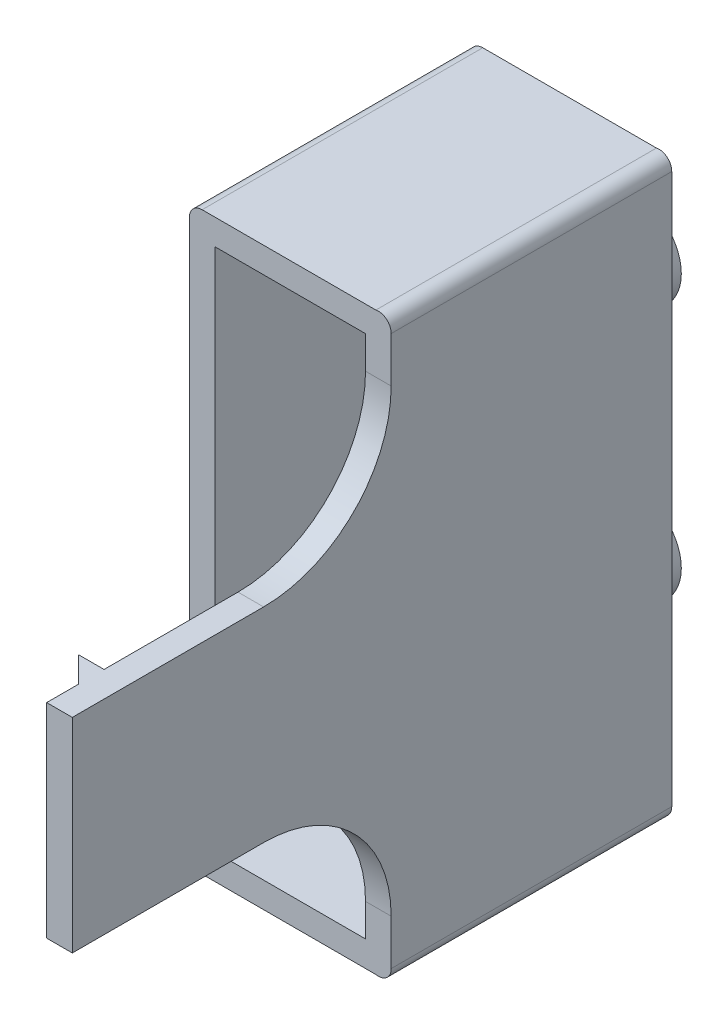
SolidWorks part; units mm, degrees
ref_plane "Front Plane" through (0, 0, 0) normal (0, 0, 1) x (1, 0, 0)
ref_plane "Top Plane" through (0, 0, 0) normal (0, 1, 0) x (1, 0, 0)
ref_plane "Right Plane" through (0, 0, 0) normal (1, 0, 0) x (0, 0, -1)
sketch "Sketch1" plane through (0, 0, 0) normal (0, 0, 1) x (1, 0, 0)
  circle A0 centre (0, -9.9992) radius 3.66
  circle A1 centre (0, 9.9992) radius 3.66
  circle A2 centre (0, -9.9992) radius 1.65
  circle A3 centre (0, 9.9992) radius 1.65
extrude "Boss-Extrude1" add sketch "Sketch1" along normal blind 5
sketch "Sketch2" plane through (0, 0, 5) normal (0, 0, 1) x (1, 0, 0)
  line L1 (-6.91, 22.56) -> (6.71, 22.56)
  line L2 (-7.91, 21.56) -> (-7.91, -21.56)
  line L3 (-6.91, -22.56) -> (6.71, -22.56)
  line L4 (7.91, 21.56) -> (7.91, -21.56)
  arc A0 (6.71, -22.56) -> (7.91, -21.56) centre (6.9102, -21.5802) ccw
  arc A1 (-7.91, -21.56) -> (-6.91, -22.56) centre (-6.91, -21.56) ccw
  arc A2 (6.71, 22.56) -> (7.91, 21.56) centre (6.9102, 21.5802) cw
  arc A3 (-6.91, 22.56) -> (-7.91, 21.56) centre (-6.91, 21.56) ccw
  circle A4 centre (0, 9.9992) radius 1.65
  circle A5 centre (0, -9.9992) radius 1.65
extrude "Boss-Extrude2" add sketch "Sketch2" along normal blind 22
sketch "Sketch3" plane through (0, 0, 27) normal (0, 0, 1) x (1, 0, 0)
  line L1 (-5.9, 20.55) -> (5.9, 20.55)
  line L2 (-5.9, 20.55) -> (-5.9, -20.55)
  line L3 (-5.9, -20.55) -> (5.9, -20.55)
  line L4 (5.9, 20.55) -> (5.9, -20.55)
extrude "Cut-Extrude1" cut sketch "Sketch3" against normal offset from surface (20 mm away) 2 up to face at (-0.0417, 0, 5)
sketch "Sketch4" plane through (0, 0, 27) normal (0, 0, 1) x (1, 0, 0)
  line L1 (5.9, 8) -> (7.91, 8)
  line L2 (5.9, 8) -> (5.9, -8)
  line L3 (5.9, -8) -> (7.91, -8)
  line L4 (7.91, 8) -> (7.91, -8)
extrude "Boss-Extrude3" add sketch "Sketch4" along normal blind 25
fillet "Fillet1" radius 10 2 edges at (6.905, 8, 27) (6.905, -8, 27)
sketch "Sketch5" plane through (0, -8, 0) normal (0, -1, 0) x (1, 0, 0)
  line L2 (5.9, 47.5) -> (3.9, 47.5)
  line L3 (3.9, 47.5) -> (5.9, 49.5)
  line L5 (5.9, 49.5) -> (5.9, 47.5)
extrude "Boss-Extrude4" add sketch "Sketch5" against normal up to surface (16 mm away) up to face at (6.905, 8, 44.5)
